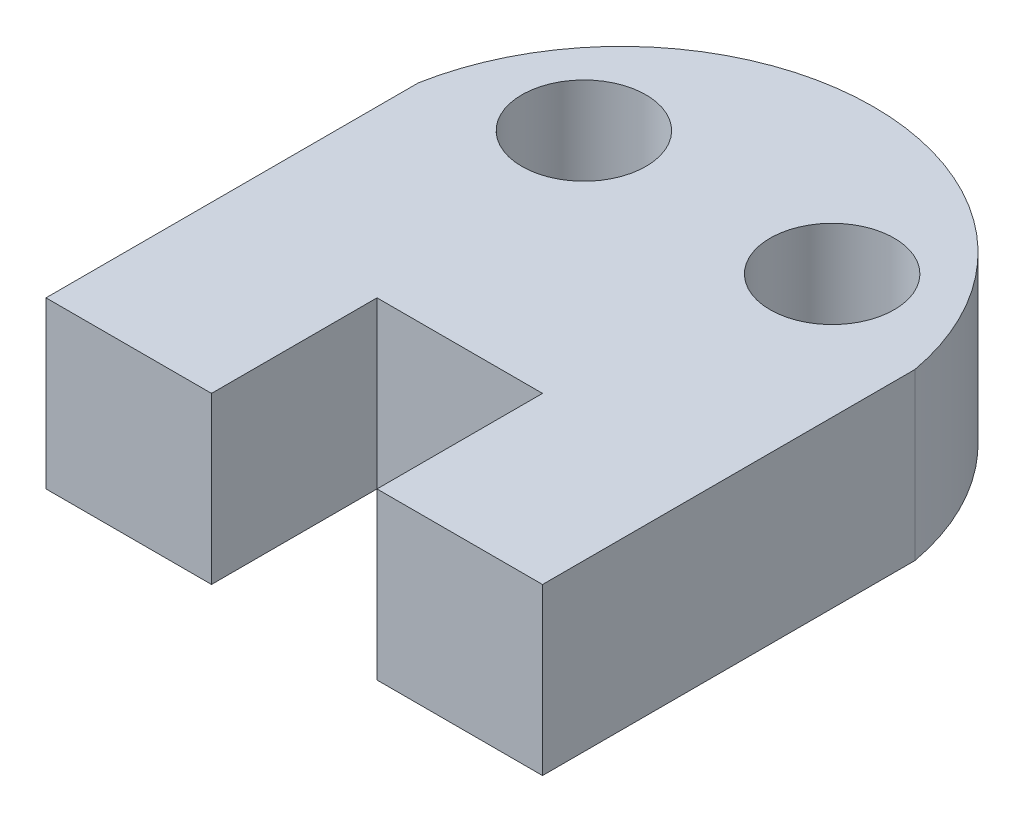
SolidWorks part; units mm, degrees
ref_plane "Front Plane" through (0, 0, 0) normal (0, 0, 1) x (1, 0, 0)
ref_plane "Top Plane" through (0, 0, 0) normal (0, 1, 0) x (1, 0, 0)
ref_plane "Right Plane" through (0, 0, 0) normal (1, 0, 0) x (0, 0, -1)
sketch "Sketch1" plane through (0, 0, 0) normal (0, 1, 0) x (1, 0, 0)
  line L0 (-6, -5) -> (-6, -9)
  line L1 (-6, 5) -> (6, 5)
  line L2 (-6, 5) -> (-6, -5)
  line L3 (-6, -5) -> (6, -5)
  line L4 (6, 5) -> (6, -5)
  line L5 (-6, 5) -> (6, -5) construction
  line L6 (-6, -5) -> (6, 5) construction
  line L7 (-6, -9) -> (-2, -9)
  line L8 (-2, -9) -> (-2, -5)
  line L9 (6, -5) -> (6, -9)
  line L10 (6, -9) -> (2, -9)
  line L11 (2, -9) -> (2, -5)
  point P0 (0, 0)
  dimension "D1" = 12
  dimension "D2" = 10
  dimension "D3" = 4
  dimension "D4" = 4
extrude "Boss-Extrude1" add sketch "Sketch1" along normal blind 4 contours L4 L1 L2 L3 | L7 L8 L3 L0 | L11 L10 L9 L3
sketch "Sketch2" plane through (0, 4, 0) normal (0, 1, 0) x (1, 0, 0)
  line L0 (-3, 1) -> (3, 1) construction
  line L1 (-6, 5) -> (6, 5) construction
  circle A0 centre (-3, 1) radius 1.5
  circle A1 centre (3, 1) radius 1.5
  point P4 (0, 1)
  dimension "D1" = 3
  dimension "D2" = 6
  dimension "D3" = 4
extrude "Cut-Extrude1" cut sketch "Sketch2" against normal through all
sketch "Sketch3" plane through (0, 4, 0) normal (0, 1, 0) x (1, 0, 0)
  line L5 (-6, 5) -> (6, 5) construction
  line L6 (-6, 5) -> (-6, -9) construction
  line L7 (6, 5) -> (6, -9) construction
  line L16 (6, -9) -> (6, 5)
  line L25 (6, 5) -> (-6, 5)
  line L26 (-6, 5) -> (-6, -9)
  line L27 (-6, -9) -> (-2, -9)
  line L36 (-2, -9) -> (-2, -5)
  line L37 (-2, -5) -> (2, -5)
  line L38 (2, -5) -> (2, -9)
  line L39 (2, -9) -> (6, -9)
  line L40 (6, 0) -> (6, 5)
  line L41 (6, 5) -> (-6, 5)
  line L42 (-6, 5) -> (-6, 0)
  arc A4 (-6, 0) -> (6, 0) centre (0, -1.1) cw
  point P0 (0, -1.1)
  point P11 (0, 0)
  point P17 (0, 0)
  line M13 (6, -9) -> (6, 5)
  line M14 (6, 5) -> (-6, 5)
  line M15 (-6, 5) -> (-6, -9)
  dimension "D1" = 5
  dimension "D2" = 5
  dimension "D3" = 0
extrude "Cut-Extrude3" cut sketch "Sketch3" against normal blind 4 contours A4 L41 M15 | A4 M14 M13
